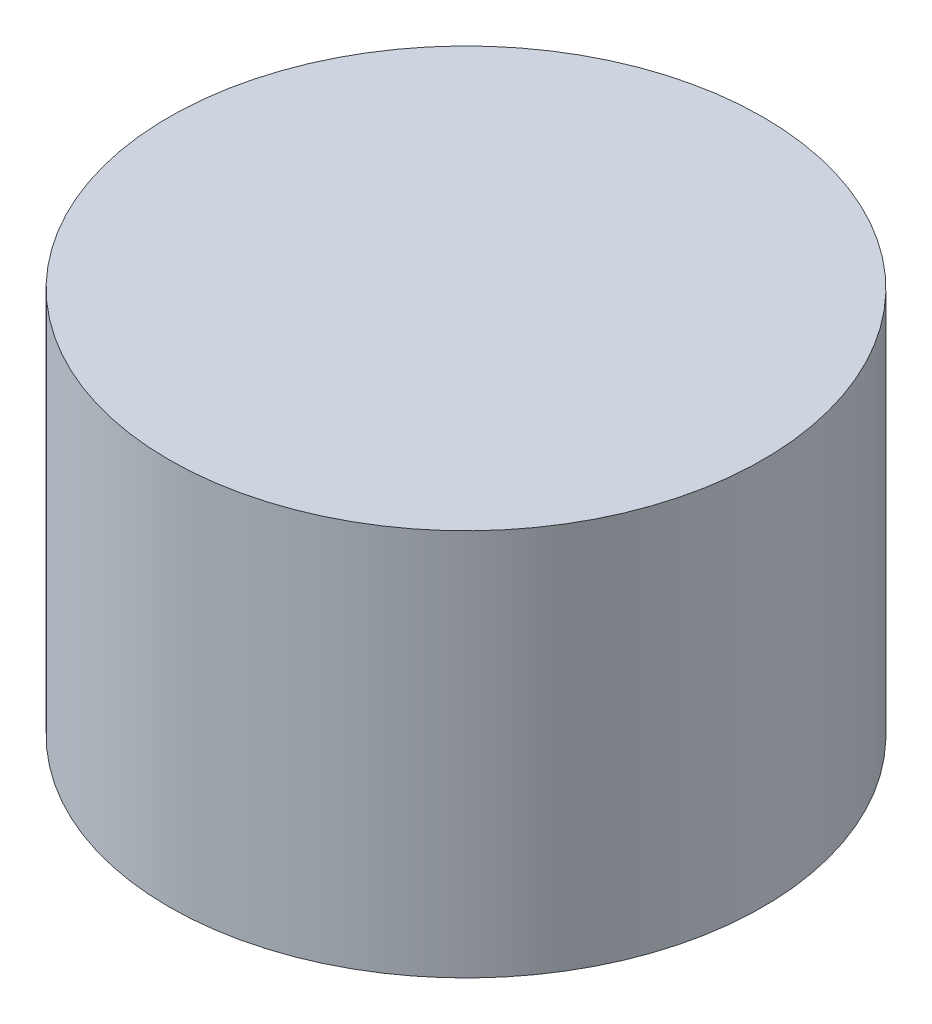
SolidWorks part; units mm, degrees
material "1.5805 (10NiCr5-4)"
ref_plane "Ebene vorne" through (0, 0, 0) normal (0, 0, 1) x (1, 0, 0)
ref_plane "Ebene oben" through (0, 0, 0) normal (0, 1, 0) x (1, 0, 0)
ref_plane "Ebene rechts" through (0, 0, 0) normal (1, 0, 0) x (0, 0, -1)
sketch "Skizze3" plane through (0, 0, 0) normal (0, 1, 0) x (1, 0, 0)
  circle A0 centre (0, 0) radius 11.5
  dimension "D1" = 23
extrude "Castor Base" add sketch "Skizze3" against normal blind 15
sketch "Skizze4" plane through (0, 0, 0) normal (0, 0, 1) x (1, 0, 0)
  line L0 (11.5, 0) -> (-11.5, 0) construction
  line L1 (0, -11.5) -> (0, 0) construction
  line L2 (0, -2) -> (0, -21)
  circle A0 centre (0, -11.5) radius 9.5
  dimension "D1" = 19
  dimension "D2" = 21
revolve "Castor Ball" add sketch "Skizze4" angle 360 about L2
